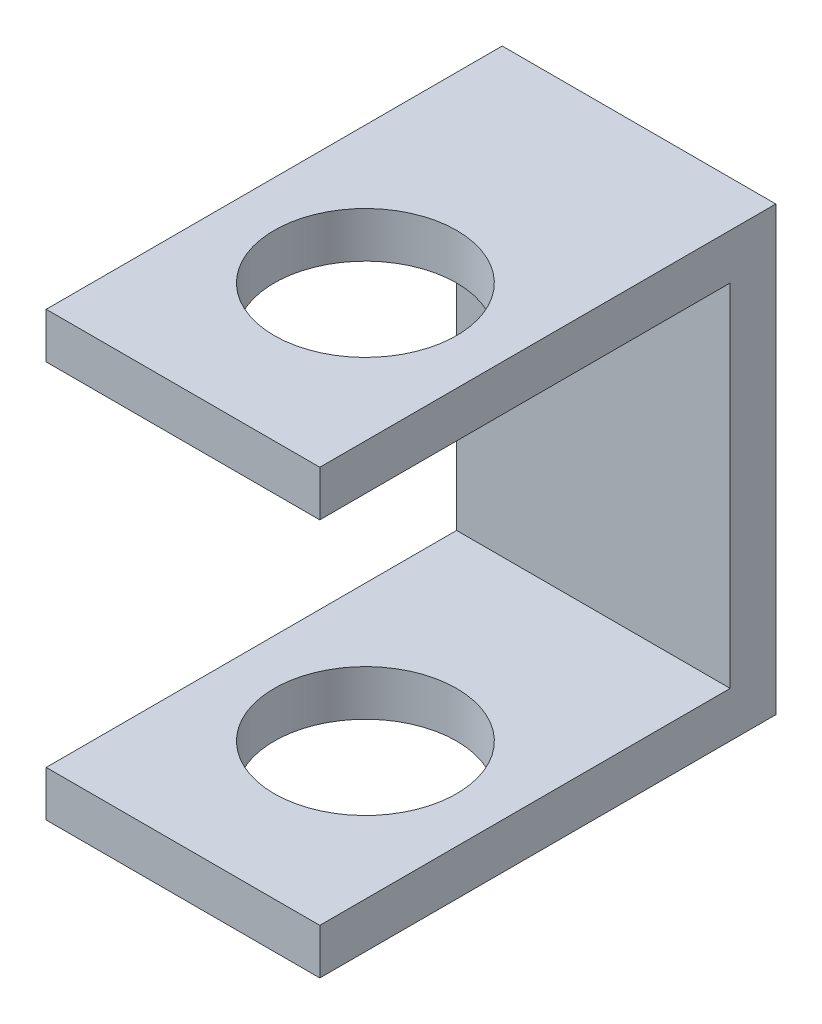
SolidWorks part; units mm, degrees
ref_plane "Front Plane" through (0, 0, 0) normal (0, 0, 1) x (1, 0, 0)
ref_plane "Top Plane" through (0, 0, 0) normal (0, 1, 0) x (1, 0, 0)
ref_plane "Right Plane" through (0, 0, 0) normal (1, 0, 0) x (0, 0, -1)
sketch "Sketch2" plane through (0, 0, 0) normal (1, 0, 0) x (0, 0, -1)
  line L0 (-63.5, 55.245) -> (-6.35, 55.245)
  line L1 (0, 0) -> (-63.5, 0)
  line L2 (0, 0) -> (0, 61.595)
  line L3 (0, 61.595) -> (-63.5, 61.595)
  line L4 (-63.5, 0) -> (-63.5, 6.35)
  line L5 (-6.35, 55.245) -> (-6.35, 6.35)
  line L6 (-6.35, 6.35) -> (-63.5, 6.35)
  line L7 (-63.5, 55.245) -> (-63.5, 61.595)
  line L8 (-6.35, 30.7975) -> (0, 30.7975) construction
  line L9 (-44.45, 79.9918) -> (-44.45, -45.9054) construction
  dimension "D1" = 48.895
  dimension "D2" = 6.35
  dimension "D3" = 38.1
  dimension "D4" = 19.05
extrude "Boss-Extrude1" add sketch "Sketch2" along normal blind 38.1
sketch "Sketch3" plane through (0, 61.595, 0) normal (0, 1, 0) x (1, 0, 0)
  line L0 (38.1, 0) -> (0, 0) construction
  circle A0 centre (19.05, -38.1) radius 12.7
  point P4 (19.05, 0)
  dimension "D2" = 25.4
  dimension "D1" = 38.1
extrude "Cut-Extrude1" cut sketch "Sketch3" against normal through all
